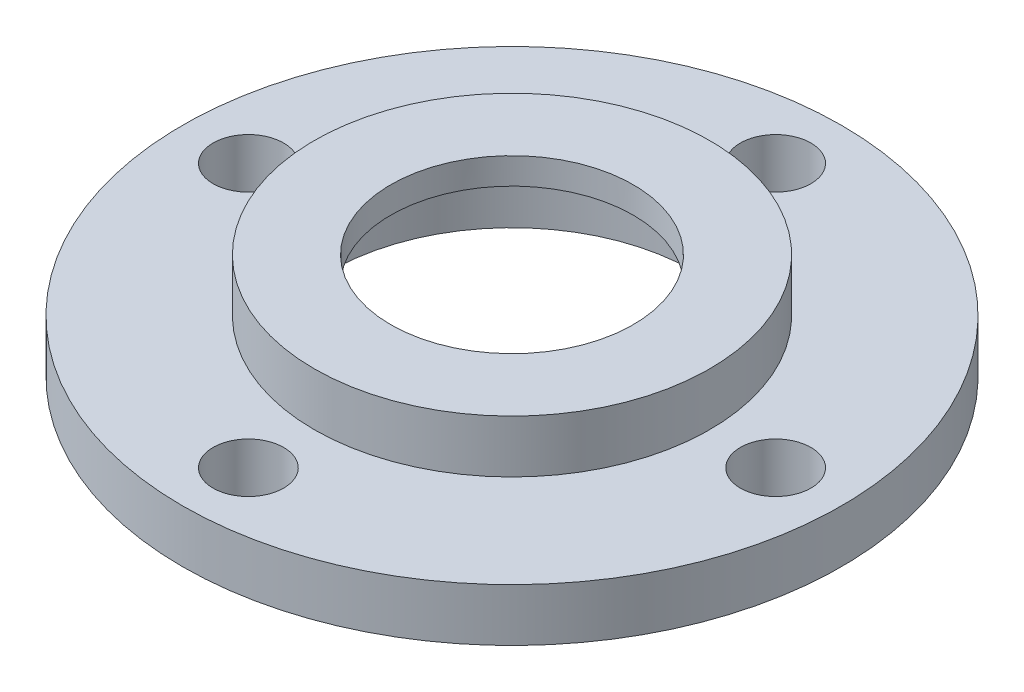
SolidWorks part; units mm, degrees
ref_plane "Front Plane" through (0, 0, 0) normal (0, 0, 1) x (1, 0, 0)
ref_plane "Top Plane" through (0, 0, 0) normal (0, 1, 0) x (1, 0, 0)
ref_plane "Right Plane" through (0, 0, 0) normal (1, 0, 0) x (0, 0, -1)
sketch "Sketch1" plane through (0, 0, 0) normal (0, 1, 0) x (1, 0, 0)
  circle A0 centre (0, 0) radius 15.875
  dimension "D1" = 31.75
extrude "Boss-Extrude1" add sketch "Sketch1" along normal blind 2.54
sketch "Sketch2" plane through (0, 2.54, 0) normal (0, 1, 0) x (1, 0, 0)
  circle A0 centre (0, 0) radius 9.525
  dimension "D1" = 19.05
extrude "Boss-Extrude2" add sketch "Sketch2" along normal blind 2.54
sketch "Sketch3" plane through (0, 0, 0) normal (0, -1, 0) x (1, 0, 0)
  circle A0 centre (0, 0) radius 8.7757
  dimension "D1" = 17.5514
extrude "Cut-Extrude1" cut sketch "Sketch3" against normal blind 3.81
sketch "Sketch4" plane through (0, 5.08, 0) normal (0, 1, 0) x (1, 0, 0)
  circle A0 centre (0, 0) radius 5.842
  dimension "D1" = 11.684
extrude "Cut-Extrude2" cut sketch "Sketch4" against normal up to next
sketch "Sketch5" plane through (0, 2.54, 0) normal (0, 1, 0) x (1, 0, 0)
  line L0 (0, 15.875) -> (0, 0) construction
  circle A0 centre (0, 12.7) radius 1.7
  circle A1 centre (0, 0) radius 15.875 construction
  circle A2 centre (12.7, 0) radius 1.7
  circle A3 centre (0, -12.7) radius 1.7
  circle A4 centre (-12.7, 0) radius 1.7
  point P18 (0, 0)
  dimension "D2" = 3.4
  dimension "D1" = 12.7
  dimension "D3" = 4
extrude "Cut-Extrude3" cut sketch "Sketch5" against normal up to next
